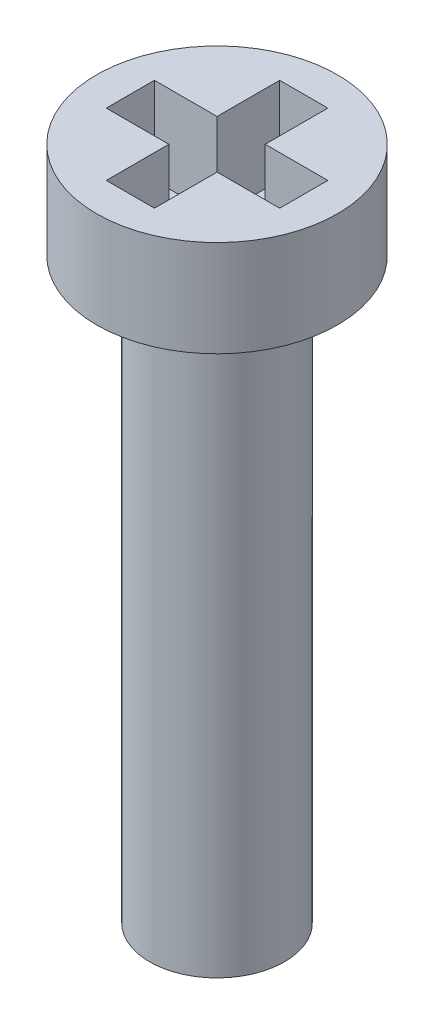
SolidWorks part; units mm, degrees
material "Plain Carbon Steel"
ref_plane "Front Plane" through (0, 0, 0) normal (0, 0, 1) x (1, 0, 0)
ref_plane "Top Plane" through (0, 0, 0) normal (0, 1, 0) x (1, 0, 0)
ref_plane "Right Plane" through (0, 0, 0) normal (1, 0, 0) x (0, 0, -1)
sketch "Sketch1" plane through (0, 0, 0) normal (0, 1, 0) x (1, 0, 0)
  line L1 (-0.9, -0.25) -> (0.9, -0.25)
  line L2 (-0.9, -0.25) -> (-0.9, 0.25)
  line L3 (-0.9, 0.25) -> (0.9, 0.25)
  line L4 (0.9, -0.25) -> (0.9, 0.25)
  line L5 (-0.9, -0.25) -> (0.9, 0.25) construction
  line L6 (-0.9, 0.25) -> (0.9, -0.25) construction
  line L7 (0.25, -0.9) -> (-0.25, -0.9)
  line L8 (0.25, -0.9) -> (0.25, 0.9)
  line L9 (0.25, 0.9) -> (-0.25, 0.9)
  line L10 (-0.25, -0.9) -> (-0.25, 0.9)
  line L11 (0.25, -0.9) -> (-0.25, 0.9) construction
  line L12 (0.25, 0.9) -> (-0.25, -0.9) construction
  circle A0 centre (0, 0) radius 1.25
  dimension "D1" = 2.5
  dimension "D2" = 0.5
  dimension "D3" = 1.8
extrude "Boss-Extrude1" add sketch "Sketch1" along normal blind 1 contours A0 L7 L10 L1 L2 L3 L9 L8 L4
sketch "Sketch2" plane through (0, 0, 0) normal (0, -1, 0) x (1, 0, 0)
  circle A1 centre (0, 0) radius 1.25
  circle A2 centre (0, 0) radius 1.25
  dimension "D1" = 0
extrude "Boss-Extrude2" add sketch "Sketch2" against normal blind 0.1
sketch "Sketch3" plane through (0, 0, 0) normal (0, -1, 0) x (1, 0, 0)
  circle A0 centre (0, 0) radius 0.7
  dimension "D1" = 1.4
extrude "Boss-Extrude3" add sketch "Sketch3" along normal blind 6
